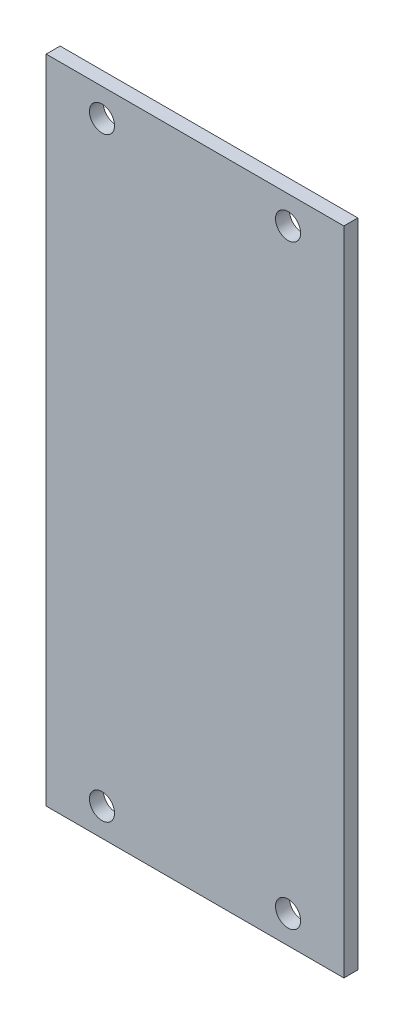
SolidWorks part; units mm, degrees
material "ABS"
ref_plane "Front Plane" through (0, 0, 0) normal (0, 0, 1) x (1, 0, 0)
ref_plane "Top Plane" through (0, 0, 0) normal (0, 1, 0) x (1, 0, 0)
ref_plane "Right Plane" through (0, 0, 0) normal (1, 0, 0) x (0, 0, -1)
sketch "Sketch1" plane through (0, 0, 0) normal (0, 0, 1) x (1, 0, 0)
  line L0 (26, 15) -> (26, -125) construction
  line L1 (0, 0) -> (52, 0)
  line L2 (0, 0) -> (0, -110)
  line L3 (0, -110) -> (52, -110)
  line L4 (52, 0) -> (52, -110)
  line L5 (-6, 15) -> (58, 15)
  line L6 (-6, 15) -> (-6, -125)
  line L7 (-6, -125) -> (58, -125)
  line L8 (58, 15) -> (58, -125)
  line L9 (-6, -55) -> (58, -55) construction
  circle A0 centre (6, 9) radius 2.6993
  circle A1 centre (46, 9) radius 2.6993
  circle A2 centre (46, -119) radius 2.6993
  circle A3 centre (6, -119) radius 2.6993
  point P9 (26, -125)
  point P10 (26, -110)
  point P11 (-6, -55)
  point P12 (0, -55)
  dimension "D1" = 52
  dimension "D2" = 110
  dimension "D3" = 64
  dimension "D4" = 140
  dimension "D5" = 12
  dimension "D6" = 6
extrude "Boss-Extrude1" add sketch "Sketch1" along normal blind 3 contours L8 L5 L6 L7 A1 A0 L1 L4 L3 L2 A2 A3 | L4 L1 L2 L3
equation "\"Depth\"= 90mm"
equation "\"Height\"= 140mm"
equation "\"Width\"= 64mm"
equation "\"D3@Sketch1\"=\"Width\""
equation "\"D4@Sketch1\"=\"Height\""
